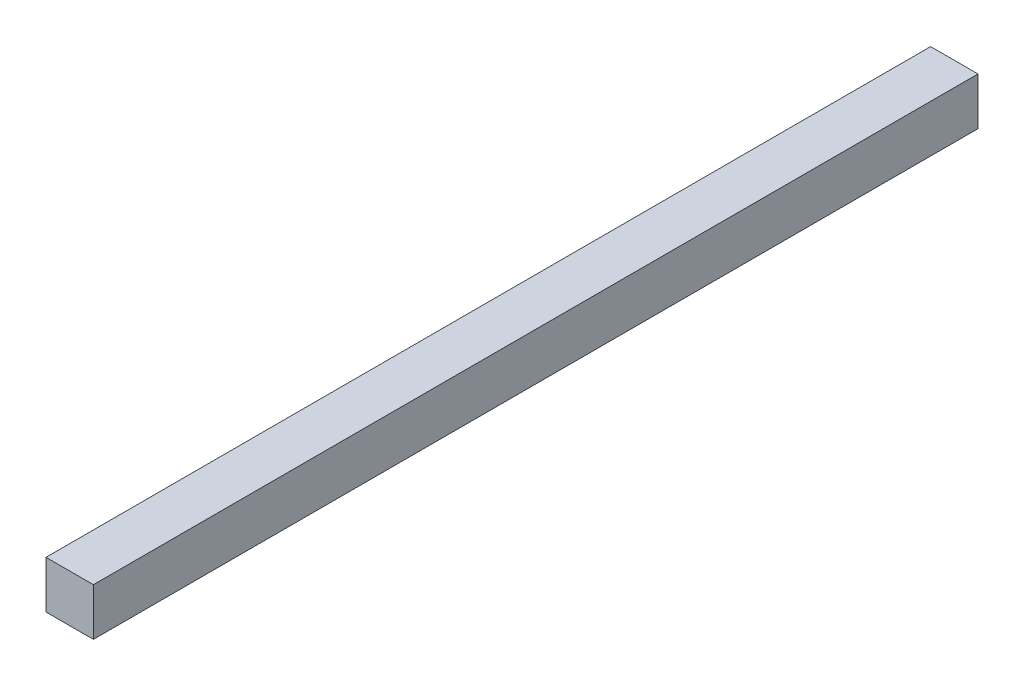
SolidWorks part; units mm, degrees
ref_plane "Front Plane" through (0, 0, 0) normal (0, 0, 1) x (1, 0, 0)
ref_plane "Top Plane" through (0, 0, 0) normal (0, 1, 0) x (1, 0, 0)
ref_plane "Right Plane" through (0, 0, 0) normal (1, 0, 0) x (0, 0, -1)
sketch "Sketch1" plane through (0, 0, 0) normal (0, 0, 1) x (1, 0, 0)
  line L1 (-15, 15) -> (15, 15)
  line L2 (-15, 15) -> (-15, -15)
  line L3 (-15, -15) -> (15, -15)
  line L4 (15, 15) -> (15, -15)
  line L5 (-15, 15) -> (15, -15) construction
  line L6 (-15, -15) -> (15, 15) construction
  point P0 (0, 0)
  dimension "D1" = 30
  dimension "D2" = 30
extrude "Boss-Extrude1" add sketch "Sketch1" along normal blind 560
